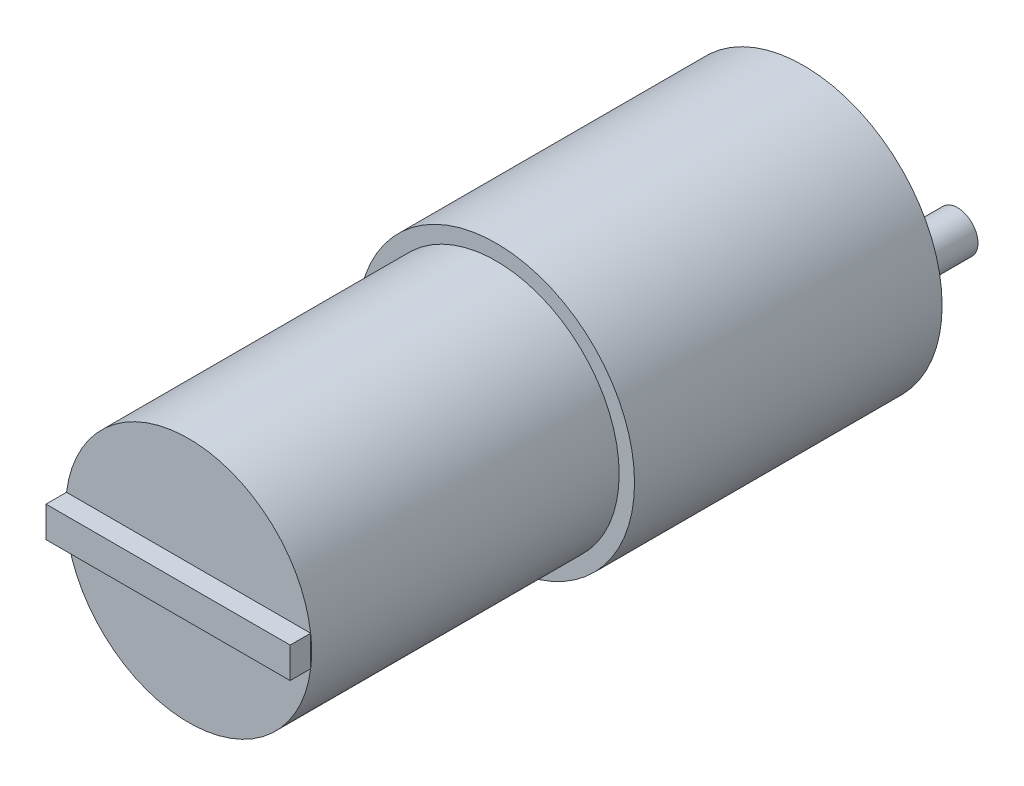
SolidWorks part; units mm, degrees
ref_plane "Front Plane" through (0, 0, 0) normal (0, 0, 1) x (1, 0, 0)
ref_plane "Top Plane" through (0, 0, 0) normal (0, 1, 0) x (1, 0, 0)
ref_plane "Right Plane" through (0, 0, 0) normal (1, 0, 0) x (0, 0, -1)
sketch "Sketch1" plane through (0, 0, 0) normal (0, 0, 1) x (1, 0, 0)
  circle A0 centre (0, 0) radius 13.5
  dimension "D1" = 27
extrude "Boss-Extrude1" add sketch "Sketch1" along normal blind 60
sketch "Sketch2" plane through (0, 0, 60) normal (0, 0, 1) x (1, 0, 0)
  circle A0 centre (0, 0) radius 12
  circle A2 centre (0, 0) radius 13.5
  circle A3 centre (0, 0) radius 13.5
  dimension "D1" = 24
  dimension "D2" = 0
extrude "Cut-Extrude1" cut sketch "Sketch2" against normal blind 30
sketch "Sketch3" plane through (0, 0, 0) normal (0, 0, -1) x (-1, 0, 0)
  circle A0 centre (0, 0) radius 2
  circle A1 centre (-8, 0) radius 2
  dimension "D1" = 4
  dimension "D2" = 4
  dimension "D3" = 8
extrude "Boss-Extrude2" add sketch "Sketch3" along normal blind 7
sketch "Sketch4" plane through (0, 0, 60) normal (0, 0, 1) x (1, 0, 0)
  line L1 (-11.9059, 1.5) -> (11.9059, 1.5)
  line L2 (-11.9059, 1.5) -> (-11.9059, -1.5)
  line L3 (-11.9059, -1.5) -> (11.9059, -1.5)
  line L4 (11.9059, 1.5) -> (11.9059, -1.5)
  circle A0 centre (0, 0) radius 12 construction
  point P9 (0.4119, -1.9667)
  dimension "D1" = 3
  dimension "D2" = 1.5
extrude "Boss-Extrude3" add sketch "Sketch4" along normal blind 2
